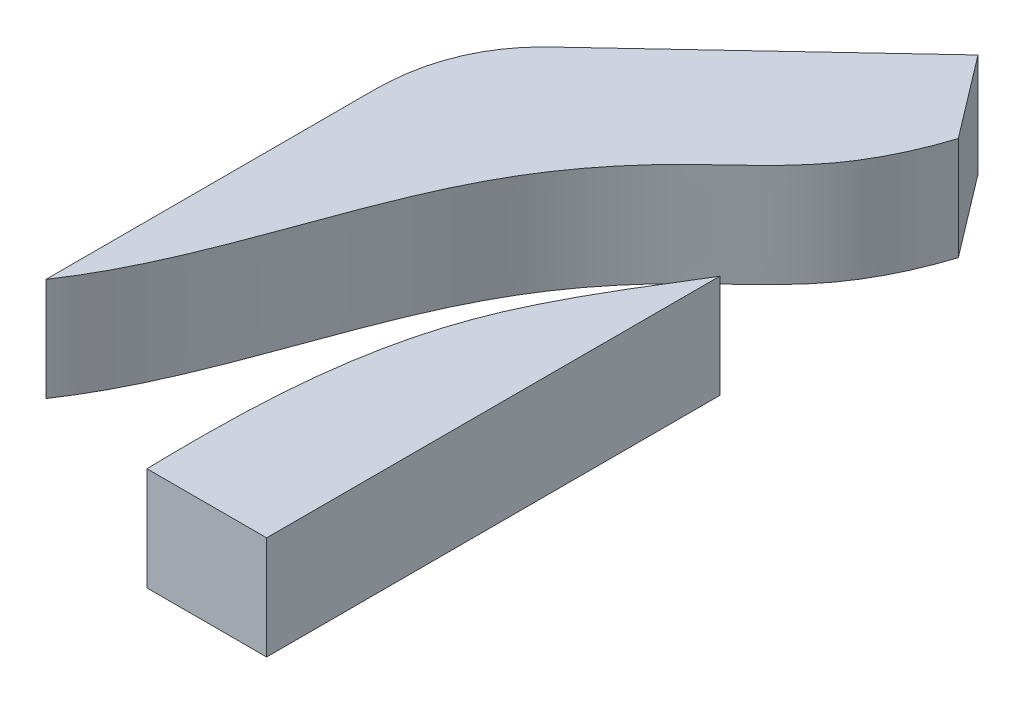
SolidWorks part; units mm, degrees
ref_plane "Front Plane" through (0, 0, 0) normal (0, 0, 1) x (1, 0, 0)
ref_plane "Top Plane" through (0, 0, 0) normal (0, 1, 0) x (1, 0, 0)
ref_plane "Right Plane" through (0, 0, 0) normal (1, 0, 0) x (0, 0, -1)
sketch "Sketch1" plane through (0, 0, 0) normal (0, 1, 0) x (1, 0, 0)
  line L0 (5.4335, -16.1487) -> (5.4335, -40.4808)
  line L3 (5.4335, 6.9546) -> (-0.6181, 14.9157)
  line L4 (-0.6181, 14.9157) -> (-21.6096, -4.7597)
  line L6 (5.4335, 6.9546) -> (5.4335, -16.1487) construction
  line L8 (-6.1594, -60.0382) -> (5.4335, -60.0382)
  line L9 (5.4335, -60.0382) -> (5.4335, -40.4808)
  line L10 (-26.9344, -17.0456) -> (-26.9344, -49.0404)
  spline S0 degree 3 poles (5.4335, 6.9546) (4.5047, 4.0568) (1.6234, -2.1734) (-6.3202, -8.5921) (-18.0784, -23.4099) (-20.3389, -39.2671) (-26.9344, -49.0404) knots 0 0 0 0 0.140998 0.305677 0.462619 1 1 1 1
  spline S1 degree 3 poles (5.4335, -16.1487) (2.4481, -21.0312) (-6.0992, -34.2629) (-6.3632, -50.6579) (-6.1594, -60.0382) knots 0 0 0 0 0.373829 1 1 1 1
  spline S2 degree 2 poles (-21.6096, -4.7597) (-26.836, -9.4266) (-26.9344, -17.0456) knots 0 0 0 1 1 1
  dimension "D2" = 10
extrude "Boss-Extrude1" add sketch "Sketch1" along normal blind 10
